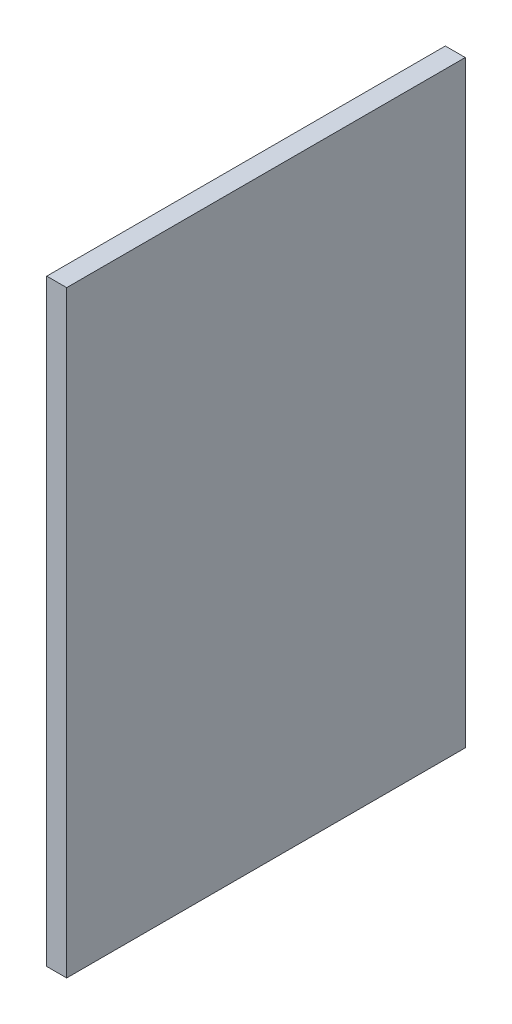
SolidWorks part; units mm, degrees
ref_plane "Alzado" through (0, 0, 0) normal (0, 0, 1) x (1, 0, 0)
ref_plane "Planta" through (0, 0, 0) normal (0, 1, 0) x (1, 0, 0)
ref_plane "Vista lateral" through (0, 0, 0) normal (1, 0, 0) x (0, 0, -1)
sketch "Croquis1" plane through (0, 0, 0) normal (0, 0, 1) x (1, 0, 0)
  line L1 (0, 0) -> (10, 0)
  line L2 (0, 0) -> (0, 300)
  line L3 (0, 300) -> (10, 300)
  line L4 (10, 0) -> (10, 300)
  dimension "D1" = 10
  dimension "D2" = 300
extrude "Saliente-Extruir1" add sketch "Croquis1" along normal blind 200
